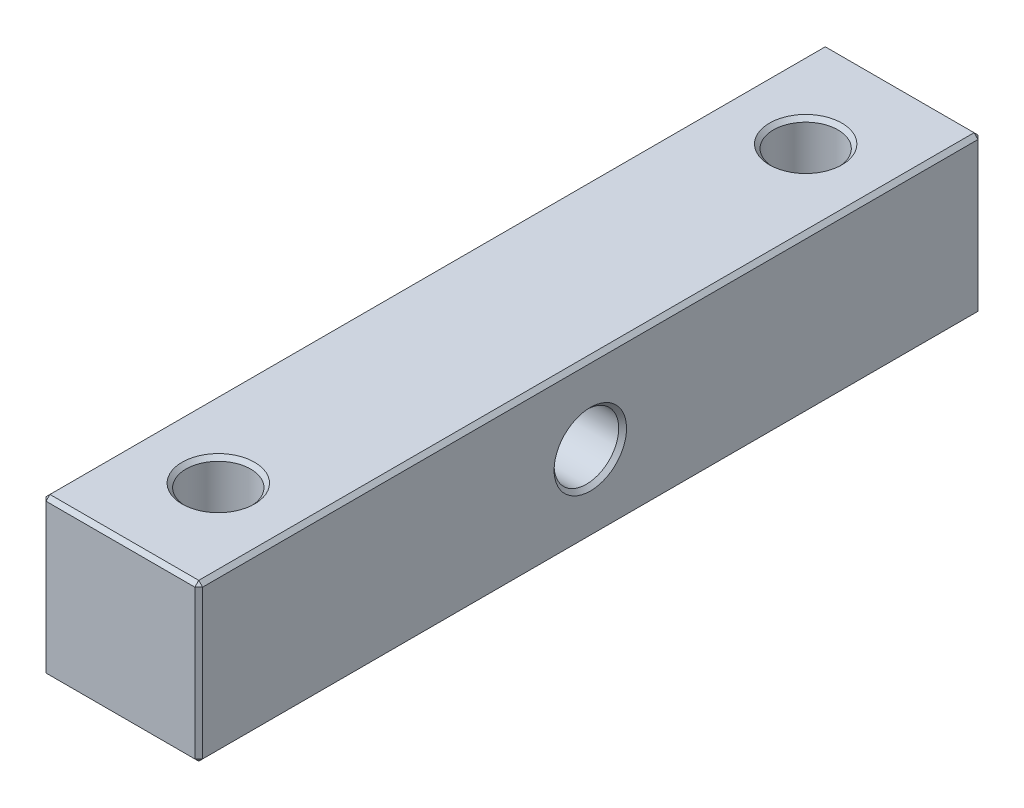
SolidWorks part; units mm, degrees
ref_plane "前视基准面" through (0, 0, 0) normal (0, 0, 1) x (1, 0, 0)
ref_plane "上视基准面" through (0, 0, 0) normal (0, 1, 0) x (1, 0, 0)
ref_plane "右视基准面" through (0, 0, 0) normal (1, 0, 0) x (0, 0, -1)
sketch "草图1" plane through (0, 0, 0) normal (0, 0, 1) x (1, 0, 0)
  line L1 (-4, 4) -> (4, 4)
  line L2 (-4, 4) -> (-4, -4)
  line L3 (-4, -4) -> (4, -4)
  line L4 (4, 4) -> (4, -4)
  line L5 (-4, 4) -> (4, -4) construction
  line L6 (-4, -4) -> (4, 4) construction
  point P0 (0, 0)
  dimension "D1" = 8
extrude "凸台-拉伸1" add sketch "草图1" along normal mid plane 40
hole_wizard "M4 螺纹孔1" positions "草图2" profile "草图3" tap size "M4" standard "GB" end condition through all
sketch "草图2" plane through (4, 0, 0) normal (1, 0, 0) x (0, 0, -1)
  line L0 (0, 0) -> (50000, 0) construction
  point P0 (0, 0)
  point P11 (0, 0)
  point P12 (0, 0)
sketch "草图3" plane through (4, 0, 0) normal (0, 1, 0) x (0, 0, -1)
  line L0 (0, 0) -> (0, 8)
  line L1 (0, 8) -> (1.65, 8)
  line L2 (1.65, 8) -> (1.65, 0)
  line L5 (1.65, 0) -> (0, 0)
  line L11 (0, -6.35) -> (0, 107.95) construction
  dimension "通孔螺纹孔钻头直径" = 3.3
  dimension "通孔螺纹孔钻头深度" = 8
cosmetic thread "孔螺蚊线3" parameters "D2"=4
hole_wizard "M4 螺纹孔2" positions "草图6" profile "草图7" tap size "M4" standard "GB" end condition through all
sketch "草图6" plane through (0, 4, 0) normal (0, 1, 0) x (1, 0, 0)
  line L0 (0, 0) -> (0, 50000) construction
  line L1 (0, 0) -> (50000, 0) construction
  point P0 (0, -15)
  point P2 (0, 15)
  dimension "D1" = 30
sketch "草图7" plane through (0, 4, 15) normal (1, 0, 0) x (0, 0, 1)
  line L0 (0, 0) -> (0, 8)
  line L1 (0, 8) -> (1.65, 8)
  line L2 (1.65, 8) -> (1.65, 0)
  line L5 (1.65, 0) -> (0, 0)
  line L11 (0, -6.35) -> (0, 107.95) construction
  dimension "通孔螺纹孔钻头直径" = 3.3
  dimension "通孔螺纹孔钻头深度" = 8
cosmetic thread "孔螺蚊线4" parameters "D2"=4
cosmetic thread "孔螺蚊线5" parameters "D2"=4
chamfer "倒角1" distance 0.2 angle 45 18 edges at (-4, 0, -1.65) (0, -4, 20) (0, -4, -20) (-4, -4, 0) (-4, 0, -20) (0, 4, 20) (-4, 4, 0) (0, 4, -20) (4, -4, 0) (4, 4, 0) (4, 0, -20) (4, 0, -1.65) (-4, 0, 20) (4, 0, 20) (0, -4, -13.35) (0, -4, 16.65) (0, 4, -13.35) (0, 4, 16.65)
